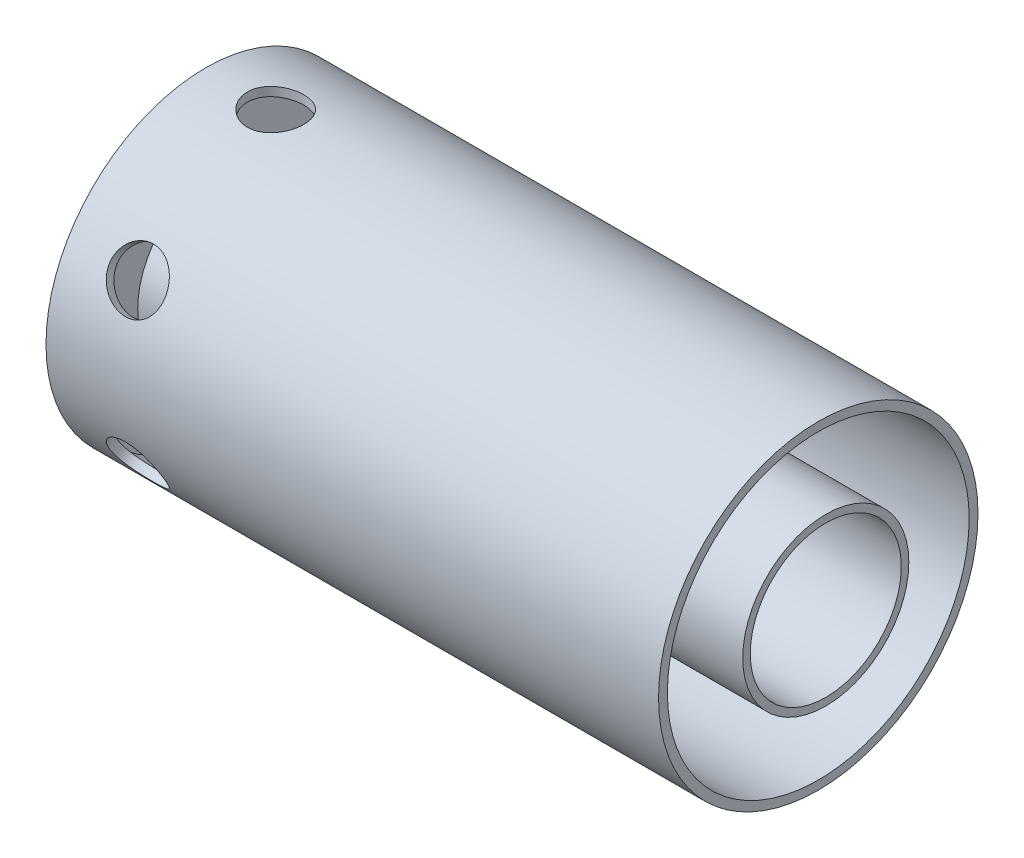
SolidWorks part; units mm, degrees
ref_plane "Front Plane" through (0, 0, 0) normal (0, 0, 1) x (1, 0, 0)
ref_plane "Top Plane" through (0, 0, 0) normal (0, 1, 0) x (1, 0, 0)
ref_plane "Right Plane" through (0, 0, 0) normal (1, 0, 0) x (0, 0, -1)
sketch "Sketch2" plane through (0, 0, 0) normal (0, 0, 1) x (1, 0, 0)
  line L0 (0.0787, 25.527) -> (0.0787, 53.975)
  line L1 (0.0787, 53.975) -> (207.0887, 53.975)
  line L2 (5.1629, 50.9905) -> (5.1629, 28.067)
  line L3 (5.1629, 50.9905) -> (207.0887, 50.9905)
  line L4 (5.1629, 28.067) -> (127, 28.067)
  line L5 (207.0887, 53.975) -> (207.0887, 50.9905)
  line L8 (209.6287, 28.067) -> (209.6287, 25.527)
  line L15 (0.0787, 25.527) -> (209.6287, 25.527)
  line L20 (0, 0) -> (168.8359, 0)
  line L25 (127, 28.067) -> (209.6287, 28.067)
  dimension "D1" = 2.54
  dimension "D2" = 207.01
  dimension "D3" = 50.9905
  dimension "D4" = 2.9845
  dimension "D5" = 25.527
  dimension "D6" = 209.55
revolve "Revolve2" add sketch "Sketch2" angle 360 about L20
ref_plane "Plane1" through (0, 53.975, 0) normal (0, 1, 0) x (1, 0, 0)
ref_plane "Plane2" through (0, -53.975, 0) normal (0, 1, 0) x (1, 0, 0)
sketch "Sketch9" plane through (0, 53.975, 0) normal (0, 1, 0) x (1, 0, 0)
  line L0 (0, 0) -> (168.8359, 0) construction
  circle A0 centre (23.7189, 0) radius 9.525
sketch "Sketch10" plane through (0, -53.975, 0) normal (0, 1, 0) x (1, 0, 0)
  circle A0 centre (23.7189, 0) radius 9.525
extrude "Cut-Extrude9" cut sketch "Sketch9" against normal blind 5.842 contours A0
extrude "Cut-Extrude10" cut sketch "Sketch10" along normal blind 40.64 contours A0
pattern_circular "CirPattern1" count 3 every 120 about axis through (0, 0, 0) along (-1, 0, 0) of "Cut-Extrude9"
pattern_circular "CirPattern2" count 3 every 120 about axis through (0, 0, 0) along (-1, 0, 0) of "Cut-Extrude10"
